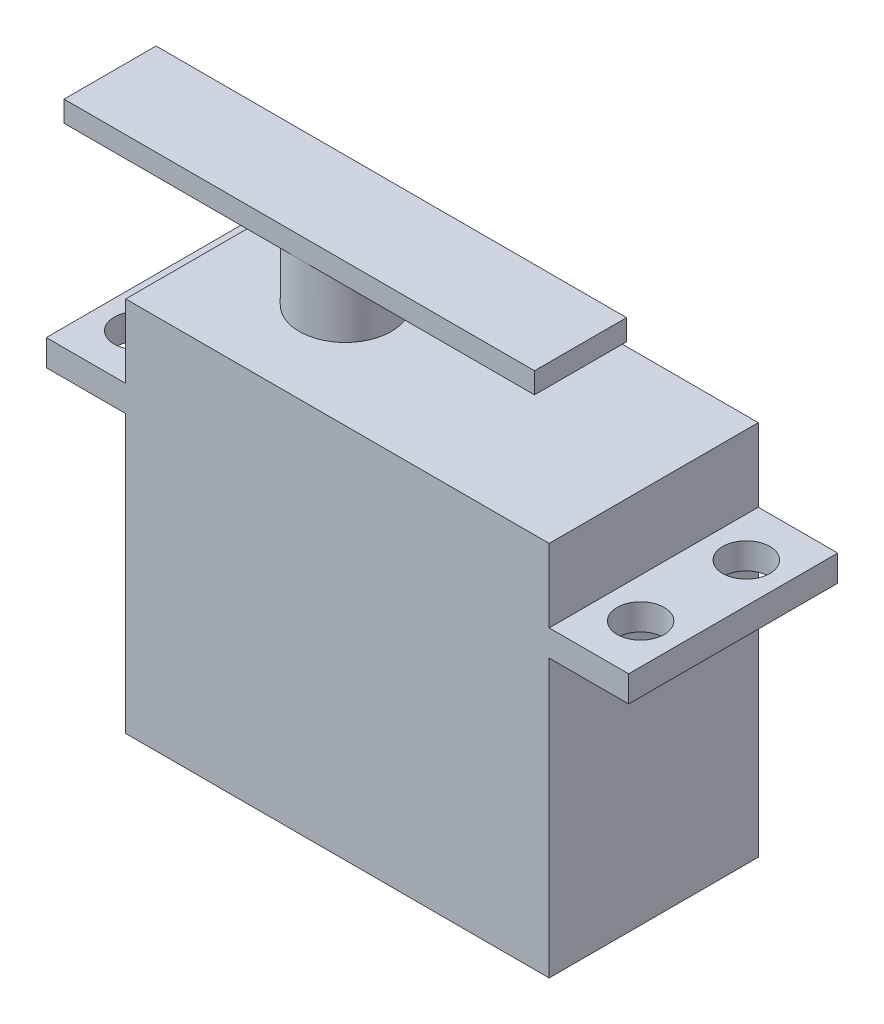
SolidWorks part; units mm, degrees
ref_plane "Front" through (0, 0, 0) normal (0, 0, 1) x (1, 0, 0)
ref_plane "Top" through (0, 0, 0) normal (0, 1, 0) x (1, 0, 0)
ref_plane "Right" through (0, 0, 0) normal (1, 0, 0) x (0, 0, -1)
sketch "Sketch1" plane through (0, 0, 0) normal (0, 0, 1) x (1, 0, 0)
  line L1 (-20.25, 18) -> (20.25, 18)
  line L2 (-20.25, 18) -> (-20.25, -18)
  line L3 (-20.25, -18) -> (20.25, -18)
  line L4 (20.25, 18) -> (20.25, -18)
  line L5 (-20.25, 18) -> (20.25, -18) construction
  line L6 (-20.25, -18) -> (20.25, 18) construction
  point P0 (0, 0)
  dimension "D1" = 40.5
  dimension "D2" = 36
extrude "Boss-Extrude1" add sketch "Sketch1" along normal mid plane 20
sketch "Sketch2" plane through (0, 0, 10) normal (0, 0, 1) x (1, 0, 0)
  line L0 (-20.25, -18) -> (20.25, -18) construction
  line L1 (-27.85, 11) -> (27.85, 11)
  line L2 (-27.85, 11) -> (-27.85, 8.5)
  line L3 (-27.85, 8.5) -> (27.85, 8.5)
  line L4 (27.85, 11) -> (27.85, 8.5)
  line L5 (-27.85, 11) -> (27.85, 8.5) construction
  line L6 (-27.85, 8.5) -> (27.85, 11) construction
  line L7 (20.25, -18) -> (20.25, 18) construction
  line L8 (-20.25, 18) -> (-20.25, -18) construction
  point P0 (0, 9.75)
  dimension "D1" = 29
  dimension "D2" = 2.5
  dimension "D3" = 7.6
  dimension "D4" = 7.6
extrude "Boss-Extrude2" add sketch "Sketch2" against normal up to surface (20 mm away) up to face at (0, 0, -10)
sketch "Sketch3" plane through (0, 18, 0) normal (0, 1, 0) x (1, 0, 0)
  line L0 (-20.25, 10) -> (-20.25, -10) construction
  circle A0 centre (-9.25, 0) radius 4.4
  dimension "D2" = 8.8
  dimension "D1" = 11
extrude "Boss-Extrude3" add sketch "Sketch3" along normal blind 8
sketch "Sketch4" plane through (0, 26, 0) normal (0, 1, 0) x (1, 0, 0)
  line L1 (-31.75, -4.4) -> (13.25, -4.4)
  line L2 (-31.75, -4.4) -> (-31.75, 4.4)
  line L3 (-31.75, 4.4) -> (13.25, 4.4)
  line L4 (13.25, -4.4) -> (13.25, 4.4)
  line L5 (-31.75, -4.4) -> (13.25, 4.4) construction
  line L6 (-31.75, 4.4) -> (13.25, -4.4) construction
  circle A0 centre (-9.25, 0) radius 4.4 construction
  point P0 (-9.25, 0)
  dimension "D1" = 45
extrude "Boss-Extrude4" add sketch "Sketch4" against normal blind 2
sketch "Sketch5" plane through (0, 8.5, 0) normal (0, -1, 0) x (1, 0, 0)
  line L0 (-24.05, 0) -> (-27.85, 0) construction
  line L1 (-24.05, -5.05) -> (24.05, -5.05) construction
  line L2 (-24.05, -5.05) -> (-24.05, 5.05) construction
  line L3 (-24.05, 5.05) -> (24.05, 5.05) construction
  line L4 (24.05, -5.05) -> (24.05, 5.05) construction
  line L5 (-24.05, -5.05) -> (24.05, 5.05) construction
  line L6 (-24.05, 5.05) -> (24.05, -5.05) construction
  line L7 (-27.85, -10) -> (-27.85, 10) construction
  line L8 (-24.05, 0) -> (-20.25, 0) construction
  line L9 (-20.25, 10) -> (-20.25, -10) construction
  circle A0 centre (-24.05, -5.05) radius 2.25
  circle A1 centre (-24.05, 5.05) radius 2.25
  circle A2 centre (24.05, -5.05) radius 2.25
  circle A3 centre (24.05, 5.05) radius 2.25
  point P8 (0, 0)
  dimension "D1" = 4.5
  dimension "D2" = 5.6
extrude "Cut-Extrude1" cut sketch "Sketch5" against normal up to surface (2.5 mm away) up to face at (-24.05, 11, 0)
